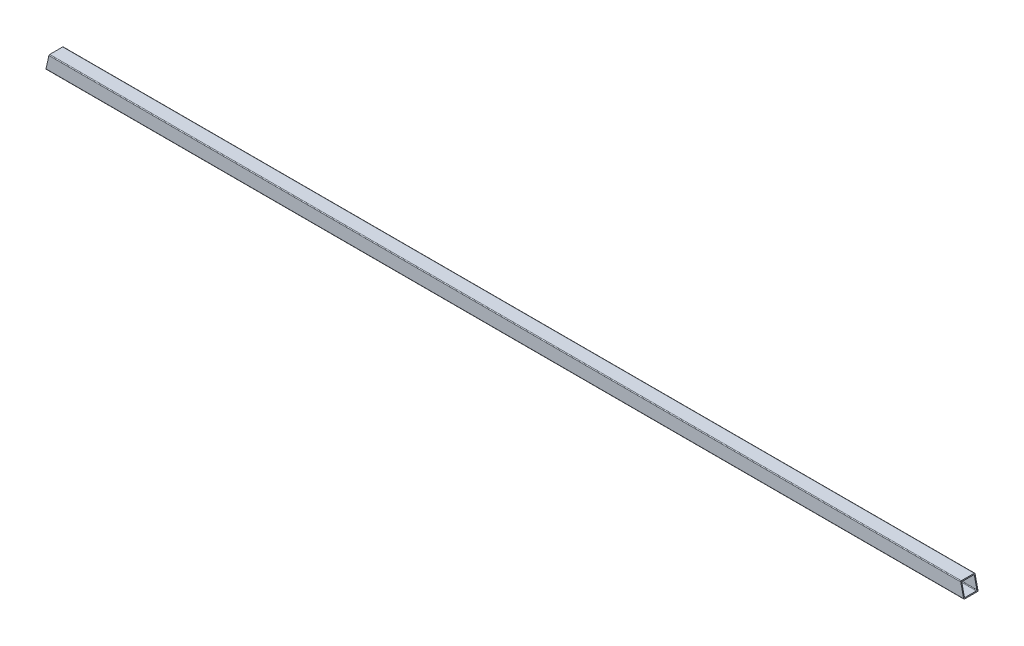
SolidWorks part; units mm, degrees
ref_plane "Front" through (0, 0, 0) normal (0, 0, 1) x (1, 0, 0)
ref_plane "Top" through (0, 0, 0) normal (0, 1, 0) x (1, 0, 0)
ref_plane "Right" through (0, 0, 0) normal (1, 0, 0) x (0, 0, -1)
sketch "Sketch1" plane through (0, 0, 0) normal (1, 0, 0) x (0, 0, -1)
  line L0 (-11.049, 0) -> (-12.7, 0) construction
  line L1 (11.43, -12.7) -> (-11.43, -12.7) construction
  line L2 (12.7, -11.43) -> (12.7, 11.43) construction
  line L3 (11.43, 12.7) -> (-11.43, 12.7) construction
  line L4 (-12.7, -11.43) -> (-12.7, 11.43) construction
  line L5 (12.7, -12.7) -> (-12.7, 12.7) construction
  line L6 (12.7, 12.7) -> (-12.7, -12.7) construction
  line L7 (9.9441, 11.049) -> (-9.9441, 11.049) construction
  line L8 (11.049, 9.9441) -> (11.049, -9.9441) construction
  line L9 (9.9441, -11.049) -> (-9.9441, -11.049) construction
  line L10 (-11.049, 9.9441) -> (-11.049, -9.9441) construction
  line L11 (11.049, 11.049) -> (-11.049, -11.049) construction
  line L12 (11.049, -11.049) -> (-11.049, 11.049) construction
  line L13 (0, -11.049) -> (0, -12.7) construction
  line L14 (11.049, -9.9441) -> (11.049, -12.7) construction
  line L15 (11.049, 0) -> (12.7, 0) construction
  line L16 (11.049, -12.7) -> (12.7, -12.7) construction
  arc A0 (-9.9441, -11.049) -> (-11.049, -9.9441) centre (-9.9441, -9.9441) cw construction
  arc A1 (11.049, -9.9441) -> (9.9441, -11.049) centre (9.9441, -9.9441) cw construction
  arc A2 (9.9441, 11.049) -> (11.049, 9.9441) centre (9.9441, 9.9441) cw construction
  arc A3 (-9.9441, 11.049) -> (-11.049, 9.9441) centre (-9.9441, 9.9441) ccw construction
  arc A4 (11.43, -12.7) -> (12.7, -11.43) centre (11.43, -11.43) ccw construction
  arc A5 (12.7, 11.43) -> (11.43, 12.7) centre (11.43, 11.43) ccw construction
  arc A6 (-11.43, 12.7) -> (-12.7, 11.43) centre (-11.43, 11.43) ccw construction
  arc A7 (-11.43, -12.7) -> (-12.7, -11.43) centre (-11.43, -11.43) cw construction
  point P0 (0, 0)
  point P6 (0, 0)
  dimension "D2" = 1.1049
  dimension "D3" = 1.27
  dimension "Outside Width" = 25.4
  dimension "Ouside Height" = 25.4
  dimension "Inside Height" = 22.098
  dimension "Wall Thickness" = 1.651
sketch "Sketch2" plane through (0, 0, 0) normal (0, 0, 1) x (1, 0, 0)
  line L0 (-812.8, 0) -> (812.8, 0) construction
  point P3 (-789.051, 0)
  point P4 (789.051, 0)
  dimension "Length" = 1625.6
  dimension "D1" = 23.749
  dimension "D2" = 23.749
sketch "Sketch4" plane through (0, 0, 0) normal (1, 0, 0) x (0, 0, -1)
  line L8 (12.7, -11.43) -> (12.7, 11.43)
  line L9 (11.43, 12.7) -> (-11.43, 12.7)
  line L10 (-12.7, -11.43) -> (-12.7, 11.43)
  line L11 (11.43, -12.7) -> (-11.43, -12.7)
  line L12 (11.049, 9.9441) -> (11.049, -9.9441)
  line L13 (9.9441, -11.049) -> (-9.9441, -11.049)
  line L14 (-11.049, 9.9441) -> (-11.049, -9.9441)
  line L15 (9.9441, 11.049) -> (-9.9441, 11.049)
  arc A8 (12.7, 11.43) -> (11.43, 12.7) centre (11.43, 11.43) ccw
  arc A9 (-11.43, 12.7) -> (-12.7, 11.43) centre (-11.43, 11.43) ccw
  arc A10 (-12.7, -11.43) -> (-11.43, -12.7) centre (-11.43, -11.43) ccw
  arc A11 (11.43, -12.7) -> (12.7, -11.43) centre (11.43, -11.43) ccw
  arc A12 (9.9441, -11.049) -> (11.049, -9.9441) centre (9.9441, -9.9441) ccw
  arc A13 (-11.049, -9.9441) -> (-9.9441, -11.049) centre (-9.9441, -9.9441) ccw
  arc A14 (-9.9441, 11.049) -> (-11.049, 9.9441) centre (-9.9441, 9.9441) ccw
  arc A15 (11.049, 9.9441) -> (9.9441, 11.049) centre (9.9441, 9.9441) ccw
extrude "Boss-Extrude1" add sketch "Sketch4" along normal up to vertex (812.8 mm away) and the other way up to vertex (812.8 mm away)
sketch "Sketch5" plane through (0, 0, 12.7) normal (0, 0, 1) x (1, 0, 0)
  line L0 (812.8, -12.7) -> (807.169, 12.7)
  line L1 (812.8, 12.7) -> (-812.8, 12.7) construction
  line L2 (807.169, 12.7) -> (812.8, 12.7)
  line L3 (812.8, 12.7) -> (812.8, -12.7)
  dimension "D1" = 12.5
extrude "Cut-Extrude1" cut sketch "Sketch5" against normal through all
mirror "Mirror1" about plane through (0, 0, 0) normal (1, 0, 0) of "Cut-Extrude1"
equation "\"D3@Sketch1\"=\"Outside Width@Sketch1\"*.05"
equation "\"D2@Sketch1\" = \"Inside Height@Sketch1\" * .05"
equation "\"D1@Sketch2\"=\"Outside Width@Sketch1\"-\"Wall Thickness@Sketch1\""
equation "\"D2@Sketch2\"=\"D1@Sketch2\""
equation "\"MidLength\"=64"
equation "\"Length@Sketch2\"=\"MidLength\""
equation "\"Angle\"=12.5"
equation "\"D1@Sketch5\"=\"Angle\""
